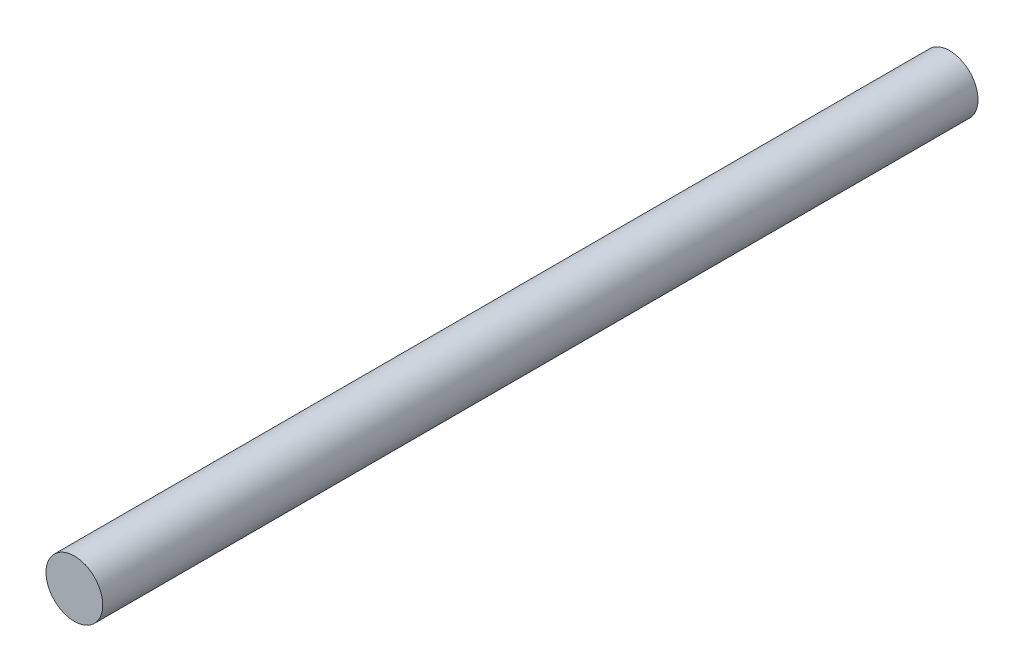
SolidWorks part; units mm, degrees
ref_plane "Front Plane" through (0, 0, 0) normal (0, 0, 1) x (1, 0, 0)
ref_plane "Top Plane" through (0, 0, 0) normal (0, 1, 0) x (1, 0, 0)
ref_plane "Right Plane" through (0, 0, 0) normal (1, 0, 0) x (0, 0, -1)
sketch "Sketch1" plane through (0, 0, 0) normal (0, 0, 1) x (1, 0, 0)
  line L0 (177.2866, 38.2939) -> (177.2866, 19.2439) construction
  line L1 (177.2866, 19.2439) -> (139.1866, 19.2439) construction
  line L2 (100.337, 38.2939) -> (47.8751, 38.2939) construction
  circle A0 centre (139.1866, 19.2439) radius 11.1125
  dimension "D3" = 22.225
  dimension "D1" = 19.05
  dimension "D2" = 38.1
extrude "Boss-Extrude1" add sketch "Sketch1" along normal up to surface (342.9 mm away) contours A0
